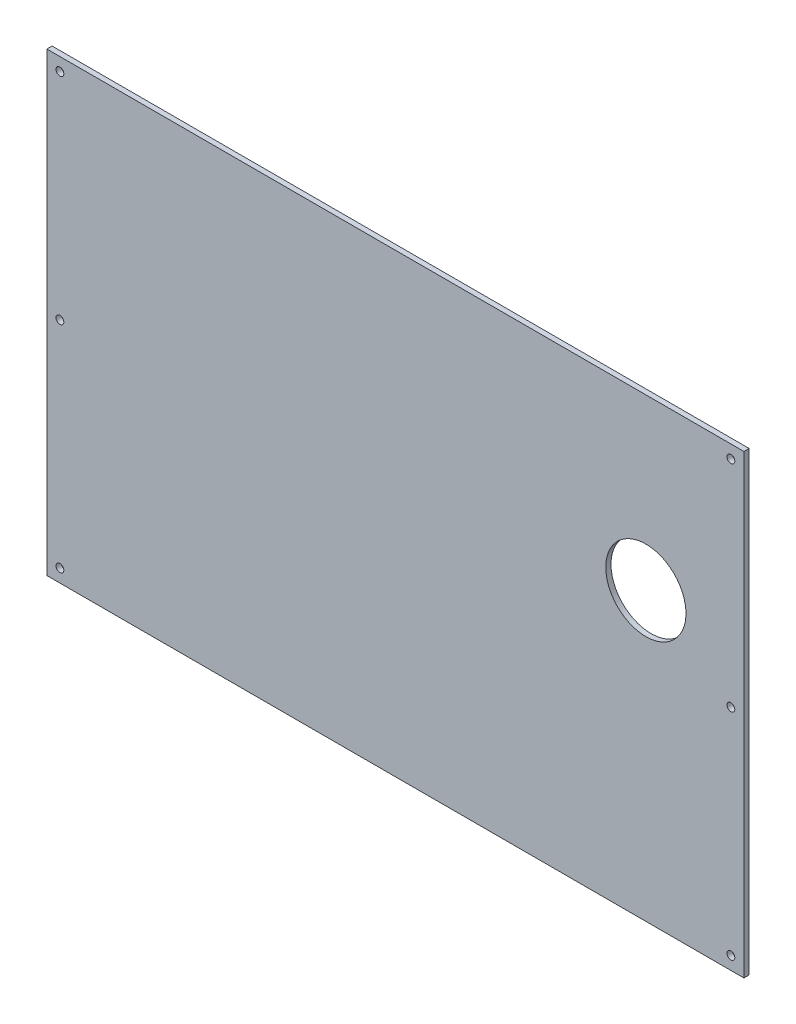
SolidWorks part; units mm, degrees
material "Sklo"
ref_plane "Přední rovina" through (0, 0, 0) normal (0, 0, 1) x (1, 0, 0)
ref_plane "Horní rovina" through (0, 0, 0) normal (0, 1, 0) x (1, 0, 0)
ref_plane "Pravá rovina" through (0, 0, 0) normal (1, 0, 0) x (0, 0, -1)
sketch "Skica1" plane through (0, 0, 0) normal (0, 0, 1) x (1, 0, 0)
  line L1 (267.5, -175) -> (-267.5, -175)
  line L2 (267.5, -175) -> (267.5, 175)
  line L3 (267.5, 175) -> (-267.5, 175)
  line L4 (-267.5, -175) -> (-267.5, 175)
  line L5 (267.5, -175) -> (-267.5, 175) construction
  line L6 (267.5, 175) -> (-267.5, -175) construction
  circle A0 centre (-257.5, 165) radius 3
  circle A1 centre (-257.5, 0) radius 3
  circle A2 centre (-257.5, -165) radius 3
  circle A3 centre (257.5, 165) radius 3
  circle A4 centre (257.5, 0) radius 3
  circle A5 centre (257.5, -165) radius 3
  point P0 (0, 0)
  point P12 (-267.5, 0)
  dimension "D3" = 6
  dimension "D1" = 535
  dimension "D2" = 350
  dimension "D4" = 10
  dimension "D5" = 10
  dimension "D6" = 10
  dimension "D7" = 10
  dimension "D8" = 10
  dimension "D9" = 2
extrude "Přidat vysunutím1" add sketch "Skica1" along normal blind 4
sketch "Skica2" plane through (0, 0, 0) normal (0, 0, -1) x (-1, 0, 0)
  circle A0 centre (-192.2483, 45.046) radius 30.7767
extrude "Odebrat vysunutím1" cut sketch "Skica2" against normal blind 4
